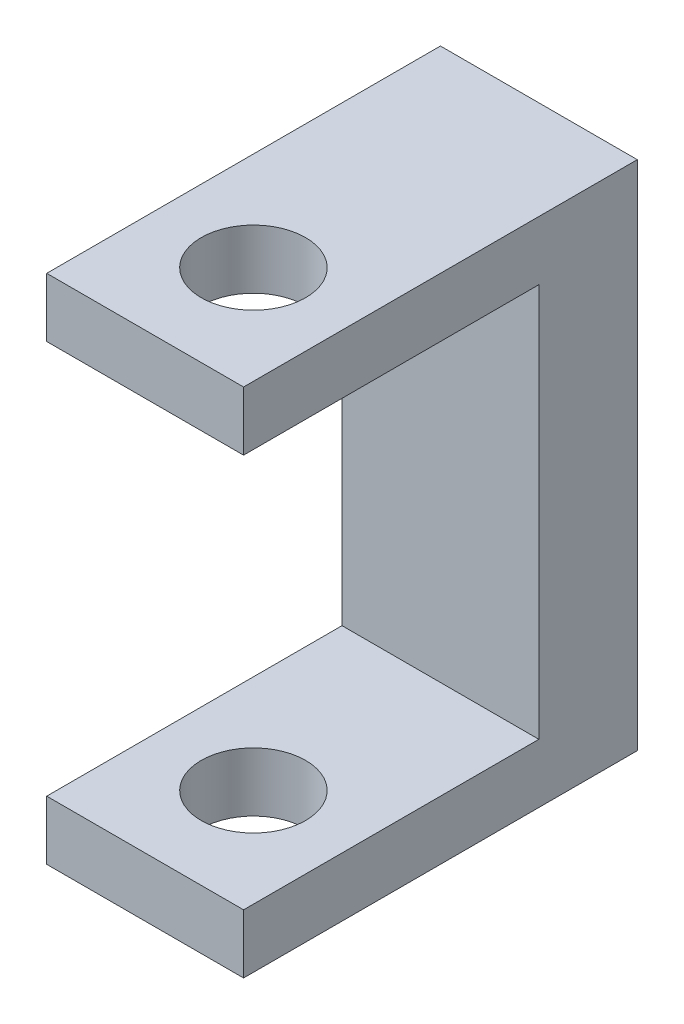
SolidWorks part; units mm, degrees
ref_plane "Front Plane" through (0, 0, 0) normal (1, 0, 0) x (0, 1, 0)
ref_plane "Top Plane" through (0, 0, 0) normal (0, 0, 1) x (0, 1, 0)
ref_plane "Right Plane" through (0, 0, 0) normal (0, 1, 0) x (-1, 0, 0)
sketch "Sketch2" plane through (0, 0, 0) normal (0, 0, 1) x (0, 1, 0)
  line L1 (-13, -5) -> (13, -5)
  line L2 (-13, -5) -> (-13, 5)
  line L3 (-13, 5) -> (13, 5)
  line L4 (13, -5) -> (13, 5)
  line L5 (-13, -5) -> (13, 5) construction
  line L6 (-13, 5) -> (13, -5) construction
  point P0 (0, 0)
extrude "Boss-Extrude1" add sketch "Sketch2" along normal blind 20
sketch "Sketch3" plane through (0, 0, 20) normal (0, 0, 1) x (1, 0, 0)
  line L0 (5, -13) -> (5, 13) construction
  line L1 (-5, 13) -> (5, 13) construction
  line L2 (-5, 13) -> (-5, 10) construction
  line L3 (-5, 10) -> (5, 10) construction
  line L4 (5, 13) -> (5, 10) construction
  line L10 (-5, -13) -> (5, -13) construction
  line L11 (-5, -13) -> (-5, -10) construction
  line L12 (-5, -10) -> (5, -10) construction
  line L13 (5, -13) -> (5, -10) construction
  line L14 (-5, 10) -> (5, 10)
  line L15 (-5, 10) -> (-5, -10)
  line L16 (-5, -10) -> (5, -10)
  line L17 (5, 10) -> (5, -10)
extrude "Cut-Extrude1" cut sketch "Sketch3" against normal blind 15
sketch "Sketch4" plane through (0, -13, 0) normal (0, -1, 0) x (1, 0, 0)
  line L1 (-5, 20) -> (0, 20)
  line L2 (-5, 20) -> (-5, 14.5)
  line L3 (-5, 14.5) -> (0, 14.5)
  line L4 (0, 20) -> (0, 14.5)
  circle A0 centre (0, 14.5) radius 2.65
extrude "Cut-Extrude2" cut sketch "Sketch4" against normal through all contours A0
